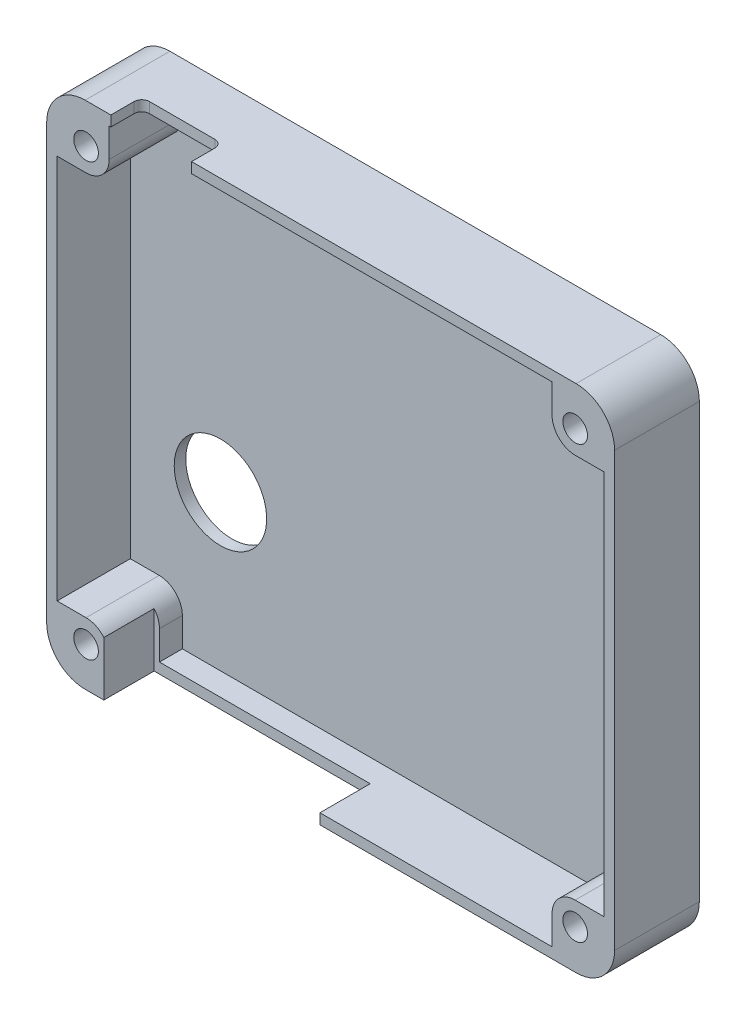
SolidWorks part; units mm, degrees
ref_plane "前视基准面" through (0, 0, 0) normal (0, 0, 1) x (1, 0, 0)
ref_plane "上视基准面" through (0, 0, 0) normal (0, 1, 0) x (1, 0, 0)
ref_plane "右视基准面" through (0, 0, 0) normal (1, 0, 0) x (0, 0, -1)
sketch "草图1" plane through (0, 0, 0) normal (0, 0, 1) x (1, 0, 0)
  line L1 (0, 0) -> (73.73, 0)
  line L2 (0, 0) -> (0, 66.24)
  line L3 (0, 66.24) -> (73.73, 66.24)
  line L4 (73.73, 0) -> (73.73, 66.24)
  dimension "D1" = 73.73
  dimension "D2" = 66.24
extrude "凸台-拉伸1" add sketch "草图1" along normal blind 11
sketch "草图5" plane through (0, 0, 0) normal (0, 0, 1) x (1, 0, 0)
  line L0 (36.865, 66.24) -> (36.865, 0) construction
  line L3 (0, 33.12) -> (73.73, 33.12) construction
  line L7 (73.73, 66.24) -> (0, 66.24) construction
  line L9 (0, 0) -> (73.73, 0) construction
  line L10 (0, 66.24) -> (0, 0) construction
  line L11 (73.73, 0) -> (73.73, 66.24) construction
  circle A0 centre (5.115, 61.125) radius 1.6
  circle A1 centre (68.615, 61.125) radius 1.6
  circle A2 centre (68.615, 5.115) radius 1.6
  circle A3 centre (5.115, 5.115) radius 1.6
  dimension "D1" = 3.2
  dimension "D2" = 63.5
  dimension "D3" = 56.01
extrude "切除-拉伸1" cut sketch "草图5" against normal through all and the other way blind 14
sketch "草图6" plane through (0, 0, 11) normal (0, 0, 1) x (1, 0, 0)
  line L0 (36.865, 66.24) -> (36.865, 0) construction
  line L1 (73.73, 66.24) -> (0, 66.24) construction
  line L2 (0, 0) -> (73.73, 0) construction
  line L3 (73.73, 33.12) -> (0, 33.12) construction
  line L4 (73.73, 0) -> (73.73, 66.24) construction
  line L5 (0, 66.24) -> (0, 0) construction
  line L6 (3.515, 61.125) -> (6.715, 61.125) construction
  line L7 (5.115, 62.725) -> (5.115, 59.525) construction
  line L8 (1.36, 58.125) -> (1.36, 8.115)
  line L9 (1.36, 4.36) -> (1.36, 61.88) construction
  line L10 (72.37, 58.125) -> (72.37, 8.115)
  line L11 (8.115, 64.88) -> (65.615, 64.88)
  line L12 (69.37, 64.88) -> (4.36, 64.88) construction
  line L13 (8.115, 1.36) -> (65.615, 1.36)
  line L14 (1.36, 58.125) -> (5.115, 58.125)
  line L15 (8.115, 64.88) -> (8.115, 61.125)
  line L16 (65.615, 64.88) -> (65.615, 61.125)
  line L17 (72.37, 58.125) -> (68.615, 58.125)
  line L18 (1.36, 8.115) -> (5.115, 8.115)
  line L19 (8.115, 1.36) -> (8.115, 5.115)
  line L20 (65.615, 1.36) -> (65.615, 5.115)
  line L21 (72.37, 8.115) -> (68.615, 8.115)
  circle A0 centre (5.115, 61.125) radius 1.6 construction
  arc A1 (8.115, 61.125) -> (5.115, 58.125) centre (5.115, 61.125) cw
  arc A2 (65.615, 61.125) -> (68.615, 58.125) centre (68.615, 61.125) ccw
  arc A3 (8.115, 5.115) -> (5.115, 8.115) centre (5.115, 5.115) ccw
  arc A4 (65.615, 5.115) -> (68.615, 8.115) centre (68.615, 5.115) cw
  point P25 (1.36, 33.12)
  point P27 (36.865, 64.88)
  dimension "D3" = 3
  dimension "D1" = 3
  dimension "D2" = 3
extrude "切除-拉伸2" cut sketch "草图6" against normal blind 9.5
sketch "草图8" plane through (0, 0, 0) normal (0, 0, 1) x (1, 0, 0)
  line L0 (36.865, 66.24) -> (36.865, 0) construction
  line L1 (18.8671, 61.7012) -> (18.8671, 55.7012)
  line L4 (17.1171, 58.7012) -> (20.6171, 58.7012)
  line L5 (24.2011, 61.7012) -> (24.2011, 55.7012)
  line L8 (22.4511, 58.7012) -> (25.9511, 58.7012)
  line L9 (9.123, 61.6901) -> (13.187, 61.6901)
  line L10 (33.3649, 61.764) -> (33.3649, 61.364)
  line L13 (73.73, 66.24) -> (0, 66.24) construction
  line L14 (0, 0) -> (73.73, 0) construction
  line L15 (40.3651, 61.764) -> (40.3651, 61.364) construction
  line L16 (64.607, 61.6901) -> (60.543, 61.6901) construction
  line L17 (51.2789, 58.7012) -> (47.7789, 58.7012) construction
  line L18 (49.5289, 61.7012) -> (49.5289, 55.7012) construction
  line L19 (56.6129, 58.7012) -> (53.1129, 58.7012) construction
  line L20 (54.8629, 61.7012) -> (54.8629, 55.7012) construction
  circle A0 centre (60.6715, 21.433) radius 6 construction
  circle A2 centre (9.123, 61.6901) radius 0.5 construction
  circle A3 centre (11.1485, 61.6901) radius 0.5 construction
  circle A4 centre (13.187, 61.6901) radius 0.5 construction
  circle A5 centre (18.8671, 58.7012) radius 2.25 construction
  circle A6 centre (24.2011, 58.7012) radius 2.25 construction
  circle A7 centre (33.3649, 61.6901) radius 0.5 construction
  circle A8 centre (40.3651, 61.6901) radius 0.5
  circle A9 centre (49.5289, 58.7012) radius 2.25
  circle A10 centre (54.8629, 58.7012) radius 2.25
  circle A11 centre (60.543, 61.6901) radius 0.5
  circle A12 centre (62.5815, 61.6901) radius 0.5
  circle A13 centre (64.607, 61.6901) radius 0.5
  circle A14 centre (13.0585, 21.433) radius 6
  point P61 (0, 0)
  dimension "D1" = 12
  dimension "D2" = 1
  dimension "D4" = 2.0385
  dimension "D5" = 4.5
  dimension "D6" = 9.123
  dimension "D3" = 2.0255
  dimension "D7" = 11.1485
  dimension "D8" = 13.0585
  dimension "D9" = 17.1171
  dimension "D10" = 18.8671
  dimension "D11" = 22.4511
  dimension "D12" = 33.3649
  dimension "D13" = 21.433
  dimension "D14" = 55.7012
  dimension "D15" = 58.7012
  dimension "D17" = 61.364
  dimension "D18" = 61.6901
  dimension "D21" = 61.764
extrude "切除-拉伸3" cut sketch "草图8" along normal blind 9 contours A12 | A11 | A13 | A10 | A9 | A8 | A14
sketch "草图10" plane through (0, 66.24, 0) normal (0, 1, 0) x (1, 0, 0)
  line L0 (13.5682, -11.1216) -> (13.5682, -7.9816) construction
  line L1 (17.0382, -11.1216) -> (10.0982, -11.1216) construction
  line L2 (10.0982, -7.9816) -> (17.0382, -7.9816) construction
  line L3 (73.73, -11) -> (0, -11) construction
  line L4 (17.8082, -6.9816) -> (9.3282, -6.9816)
  line L5 (18.8082, -7.9816) -> (18.8082, -11)
  line L6 (18.8082, -11) -> (8.3282, -11)
  line L7 (8.3282, -7.9816) -> (8.3282, -11)
  line L8 (18.0082, -8.9516) -> (18.0082, -10.1516) construction
  arc A0 (9.3282, -6.9816) -> (8.3282, -7.9816) centre (9.3282, -7.9816) ccw
  arc A1 (17.8082, -6.9816) -> (18.8082, -7.9816) centre (17.8082, -7.9816) cw
  dimension "D3" = 1
  dimension "D1" = 0.8
  dimension "D2" = 1
extrude "切除-拉伸4" cut sketch "草图10" against normal blind 9
sketch "草图11" plane through (0, 0, 0) normal (0, -1, 0) x (1, 0, 0)
  line L0 (68.4308, 11.2016) -> (5.0568, 11.2016) construction
  line L1 (35.4728, 11.2016) -> (7.4219, 11.2016)
  line L2 (35.4728, 11.2016) -> (35.4728, 4.4716)
  line L3 (35.4728, 4.4716) -> (7.4219, 4.4716)
  line L4 (7.4219, 11.2016) -> (7.4219, 4.4716)
  line L5 (33.9728, 11.0716) -> (33.9728, 7.1716) construction
  line L6 (30.7728, 5.4716) -> (22.0128, 5.4716) construction
  line L7 (8.9219, 7.0716) -> (8.9219, 6.1716) construction
  point P12 (8.9219, 6.6216)
  dimension "D1" = 1.5
  dimension "D2" = 1
  dimension "D3" = 1.5
extrude "切除-拉伸5" cut sketch "草图11" against normal blind 9
fillet "圆角1" radius 5 4 edges at (73.73, 0, 5.5) (0, 0, 5.5) (0, 66.24, 5.5) (73.73, 66.24, 5.5)
